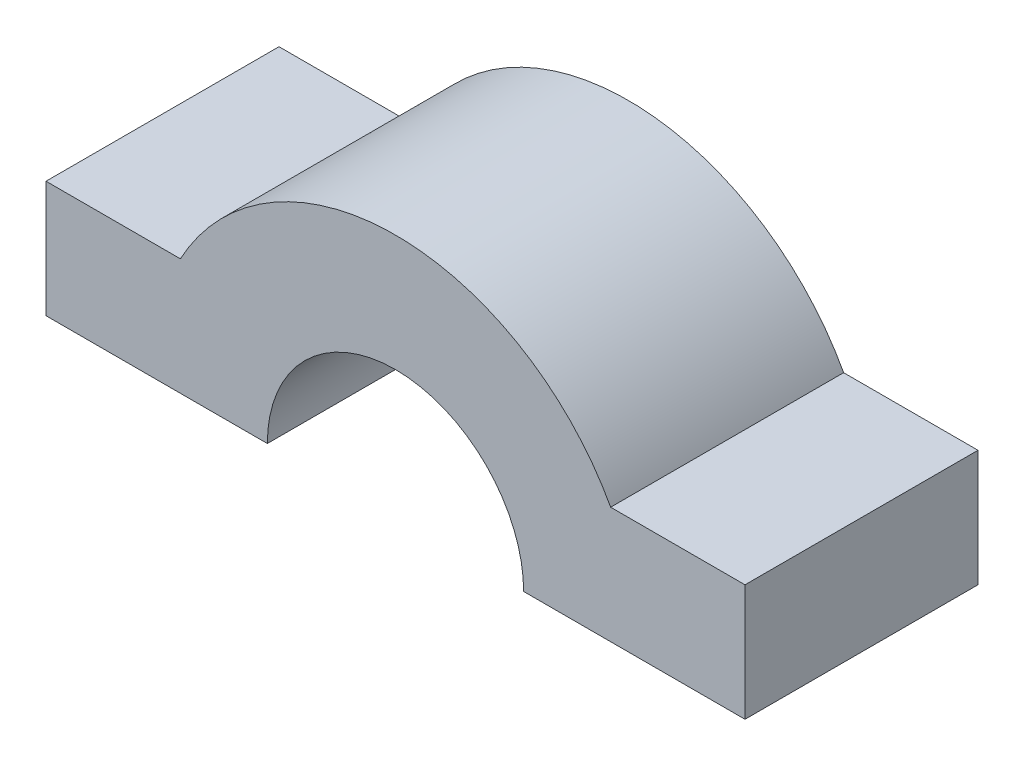
SolidWorks part; units mm, degrees
ref_plane "정면" through (0, 0, 0) normal (0, 0, 1) x (1, 0, 0)
ref_plane "윗면" through (0, 0, 0) normal (0, 1, 0) x (1, 0, 0)
ref_plane "우측면" through (0, 0, 0) normal (1, 0, 0) x (0, 0, -1)
sketch "Sketch1" plane through (0, 0, 0) normal (0, 0, 1) x (1, 0, 0)
  line L0 (-15, 0) -> (-5.5, 0)
  line L1 (5.5, 0) -> (15, 0)
  line L2 (-15, 5) -> (-9.2331, 5)
  line L3 (9.2331, 5) -> (15, 5)
  line L4 (-15, 0) -> (-15, 5)
  line L5 (15, 0) -> (15, 5)
  arc A0 (5.5, 0) -> (-5.5, 0) centre (0, 0) ccw
  arc A1 (9.2331, 5) -> (-9.2331, 5) centre (0, 0) ccw
  dimension "D1" = 11
  dimension "D2" = 30
  dimension "D3" = 5
extrude "Boss-Extrude1" add sketch "Sketch1" along normal blind 10
